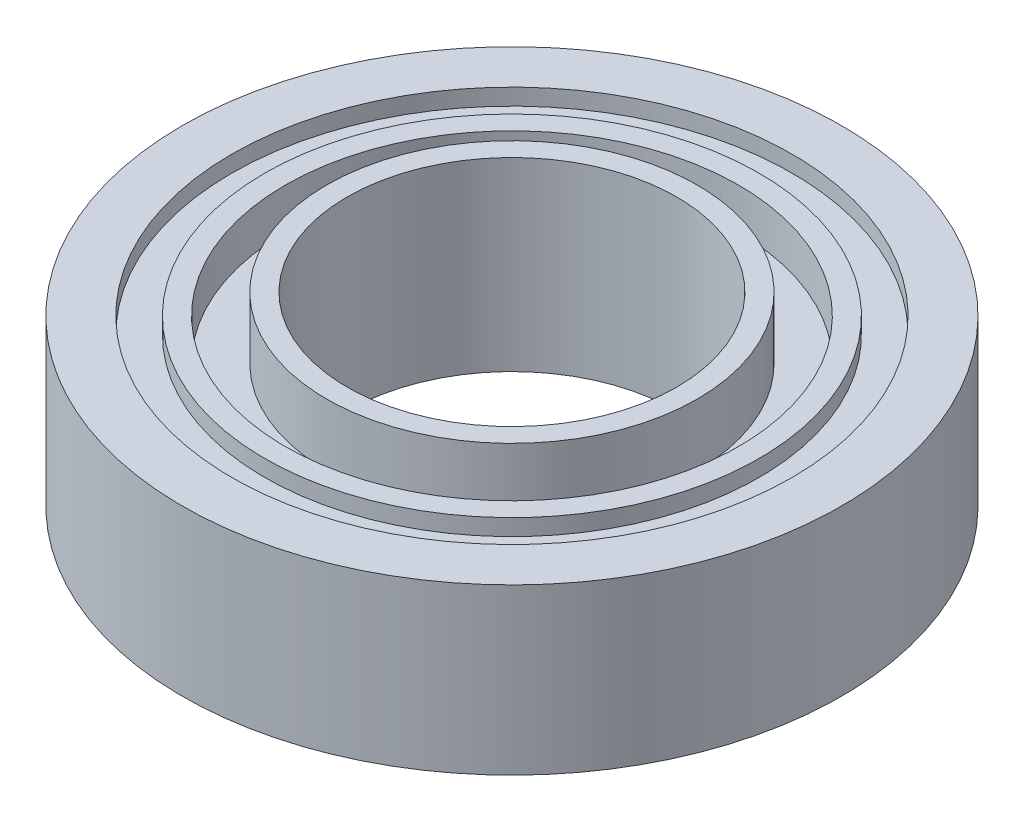
SolidWorks part; units mm, degrees
ref_plane "Front Plane" through (0, 0, 0) normal (0, 0, 1) x (1, 0, 0)
ref_plane "Top Plane" through (0, 0, 0) normal (0, 1, 0) x (1, 0, 0)
ref_plane "Right Plane" through (0, 0, 0) normal (1, 0, 0) x (0, 0, -1)
sketch "Sketch1" plane through (0, 0, 0) normal (0, 0, 1) x (1, 0, 0)
  line L0 (6.35, 25.4) -> (6.35, 12.7)
  line L1 (-25.4, 25.4) -> (-10.16, 25.4)
  line L2 (-25.4, 25.4) -> (-25.4, -25.4)
  line L3 (-25.4, -25.4) -> (7.62, -25.4)
  line L4 (25.4, 25.4) -> (25.4, -25.4)
  line L5 (-25.4, 25.4) -> (25.4, -25.4) construction
  line L6 (-25.4, -25.4) -> (25.4, 25.4) construction
  line L7 (6.35, 12.7) -> (19.05, 12.7)
  line L8 (19.05, 12.7) -> (19.05, 25.4)
  line L9 (7.62, -25.4) -> (7.62, -20.32)
  line L10 (7.62, -20.32) -> (17.78, -20.32)
  line L11 (17.78, -20.32) -> (17.78, -25.4)
  line L12 (0, 25.4) -> (6.35, 25.4)
  line L14 (-10.16, 25.4) -> (-10.16, 20.32)
  line L15 (-10.16, 20.32) -> (0, 20.32)
  line L16 (0, 25.4) -> (0, 20.32)
  line L18 (17.78, -25.4) -> (25.4, -25.4)
  line L19 (0, 0) -> (76.2, 0) construction
  line L20 (76.2, -1.3039) -> (76.2, -50001.3039) construction
  line L21 (19.05, 25.4) -> (19.05, 31.75)
  line L22 (19.05, 31.75) -> (25.4, 31.75)
  line L23 (25.4, 31.75) -> (25.4, 25.4)
  point P0 (0, 0)
  point P18 (76.2, 0)
  point P19 (12.7, -20.32)
  dimension "D1" = 10.16
  dimension "D2" = 5.08
  dimension "D3" = 12.7
  dimension "D4" = 6.35
  dimension "D5" = 12.7
  dimension "D6" = 50.8
  dimension "D7" = 50.8
  dimension "D8" = 12.7
  dimension "D10" = 76.2
  dimension "D9" = 6.35
  dimension "D11" = 6.35
revolve "Revolve1" add sketch "Sketch1" angle 360 about L20
sketch "Sketch3" plane through (0, 25.4, 0) normal (0, 1, 0) x (1, 0, 0)
  line L0 (76.2, 0) -> (76.2, -50000) construction
  line L1 (-10.16, 0) -> (-25.4, 0) construction
  circle A0 centre (76.2, 0) radius 93.98 construction
  circle A1 centre (76.2, 0) radius 86.36 construction
  circle A2 centre (76.2, 0) radius 86.36 construction
  circle A3 centre (76.2, 0) radius 101.6 construction
  point P15 (-17.78, 0)
equation "\"D2@Sketch1\"=\"D1@Sketch1\"/2"
